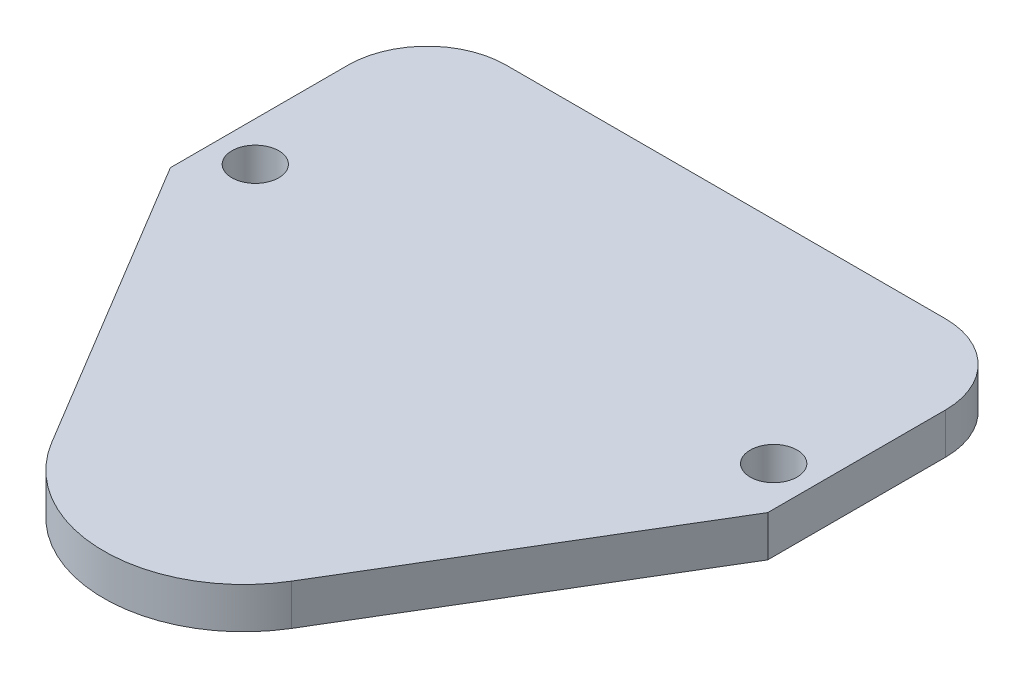
SolidWorks part; units mm, degrees
ref_plane "Front Plane" through (0, 0, 0) normal (0, 0, 1) x (1, 0, 0)
ref_plane "Top Plane" through (0, 0, 0) normal (0, 1, 0) x (1, 0, 0)
ref_plane "Right Plane" through (0, 0, 0) normal (1, 0, 0) x (0, 0, -1)
sketch "Sketch1" plane through (0, 0, 0) normal (0, 1, 0) x (1, 0, 0)
  line L0 (-58.3929, 5.5) -> (59.0732, 5.5) construction
  line L1 (-22.25, 31.5) -> (22.25, 31.5)
  line L2 (-30.25, 23.5) -> (-30.25, 5.5)
  line L4 (30.25, 23.5) -> (30.25, 5.5)
  line L5 (-30.25, 31.5) -> (3.437, -3.579) construction
  line L6 (-16.5747, -17.2596) -> (30.25, 31.5) construction
  line L7 (30.25, 5.5) -> (12.1478, -24.6271)
  line L8 (0, 0) -> (0, -45.3346) construction
  line L9 (-30.25, 5.5) -> (-12.1478, -24.6271)
  line L10 (13.8768, -14.4502) -> (16.5747, -17.2596) construction
  line L11 (0, 0) -> (0, 49.6328) construction
  line L12 (-4.4194, 10.1) -> (49.7359, 10.1) construction
  line L13 (26.25, 35.9914) -> (26.25, -9.138) construction
  arc A0 (-12.1478, -24.6271) -> (12.1478, -24.6271) centre (0, -17.328) ccw
  arc A1 (-30.25, 23.5) -> (-22.25, 31.5) centre (-22.25, 23.5) cw
  arc A2 (30.25, 23.5) -> (22.25, 31.5) centre (22.25, 23.5) ccw
  circle A3 centre (26.25, 10.1) radius 2.375
  circle A4 centre (-26.25, 10.1) radius 2.375
  point P0 (0, 0)
  dimension "D1" = 8
  dimension "D7" = 4.75
  dimension "D2" = 60.5
  dimension "D3" = 26
  dimension "D4" = 31
  dimension "D5" = 21.4
  dimension "D6" = 4
  dimension "D8" = 52.5
extrude "Boss-Extrude1" add sketch "Sketch1" along normal blind 4.15
